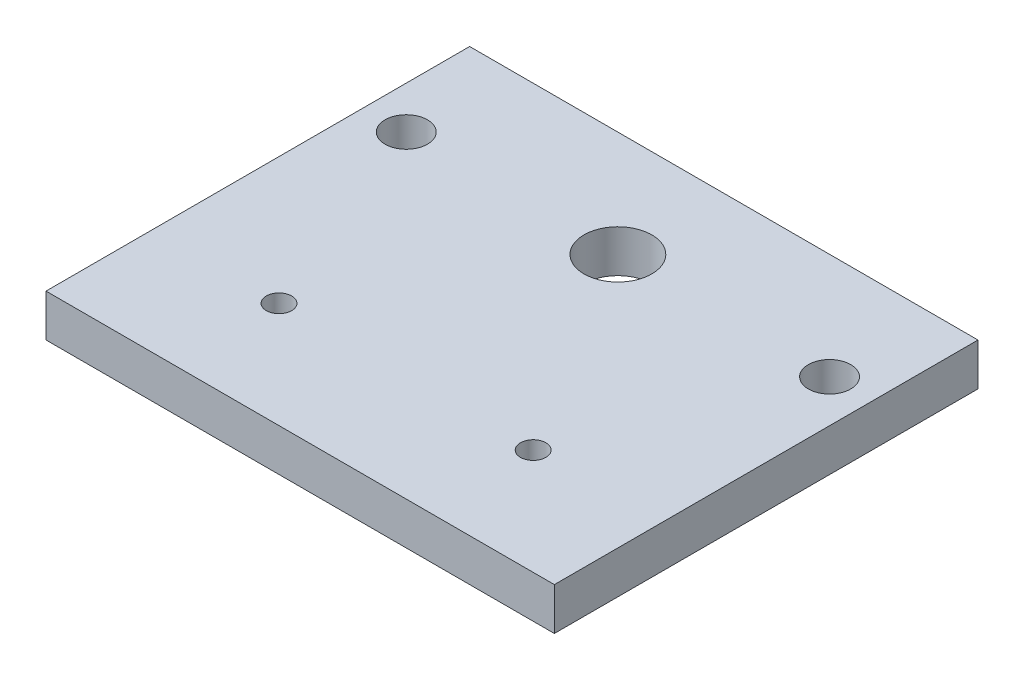
SolidWorks part; units mm, degrees
ref_plane "Front Plane" through (0, 0, 0) normal (0, 0, 1) x (1, 0, 0)
ref_plane "Top Plane" through (0, 0, 0) normal (0, 1, 0) x (1, 0, 0)
ref_plane "Right Plane" through (0, 0, 0) normal (1, 0, 0) x (0, 0, -1)
sketch "Sketch1" plane through (0, 0, 0) normal (0, 1, 0) x (1, 0, 0)
  line L0 (0, -25) -> (60, -25) construction
  line L1 (0, 0) -> (60, 0)
  line L2 (0, 0) -> (0, -50)
  line L3 (0, -50) -> (60, -50)
  line L4 (60, 0) -> (60, -50)
  line L5 (60, -25) -> (30, 0) construction
  line L6 (30, 0) -> (30, -25) construction
  line L7 (30, -12.5) -> (60, -12.5) construction
  line L8 (30, -12.5) -> (0, -12.5) construction
  line L9 (0, -50) -> (30, -25) construction
  line L10 (30, -25) -> (60, -50) construction
  line L11 (60, -50) -> (59.7781, -49.6185) construction
  circle A0 centre (30, -12.5) radius 4
  circle A1 centre (15, -37.5) radius 1.5
  circle A2 centre (45, -37.5) radius 1.5
  circle A3 centre (5, -12.4797) radius 2.5
  circle A4 centre (55, -12.5203) radius 2.5
  dimension "D3" = 8
  dimension "D4" = 3
  dimension "D5" = 3
  dimension "D1" = 50
  dimension "D2" = 60
extrude "Boss-Extrude1" add sketch "Sketch1" along normal blind 5
